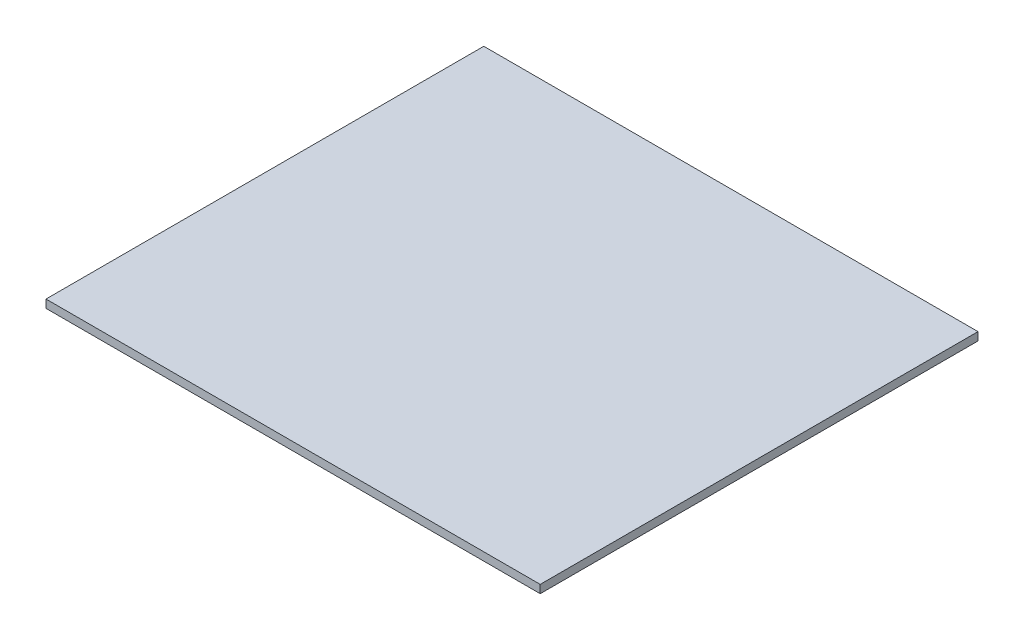
SolidWorks part; units mm, degrees
ref_plane "Front Plane" through (0, 0, 0) normal (0, 0, 1) x (1, 0, 0)
ref_plane "Top Plane" through (0, 0, 0) normal (0, 1, 0) x (1, 0, 0)
ref_plane "Right Plane" through (0, 0, 0) normal (1, 0, 0) x (0, 0, -1)
sketch "Sketch1" plane through (0, 0, 0) normal (0, 1, 0) x (1, 0, 0)
  line L1 (-152.4, 135) -> (152.4, 135)
  line L2 (-152.4, 135) -> (-152.4, -135)
  line L3 (-152.4, -135) -> (152.4, -135)
  line L4 (152.4, 135) -> (152.4, -135)
  line L5 (-152.4, 135) -> (152.4, -135) construction
  line L6 (-152.4, -135) -> (152.4, 135) construction
  point P0 (0, 0)
  dimension "D1" = 304.8
  dimension "D2" = 270
extrude "Boss-Extrude1" add sketch "Sketch1" along normal blind 5
